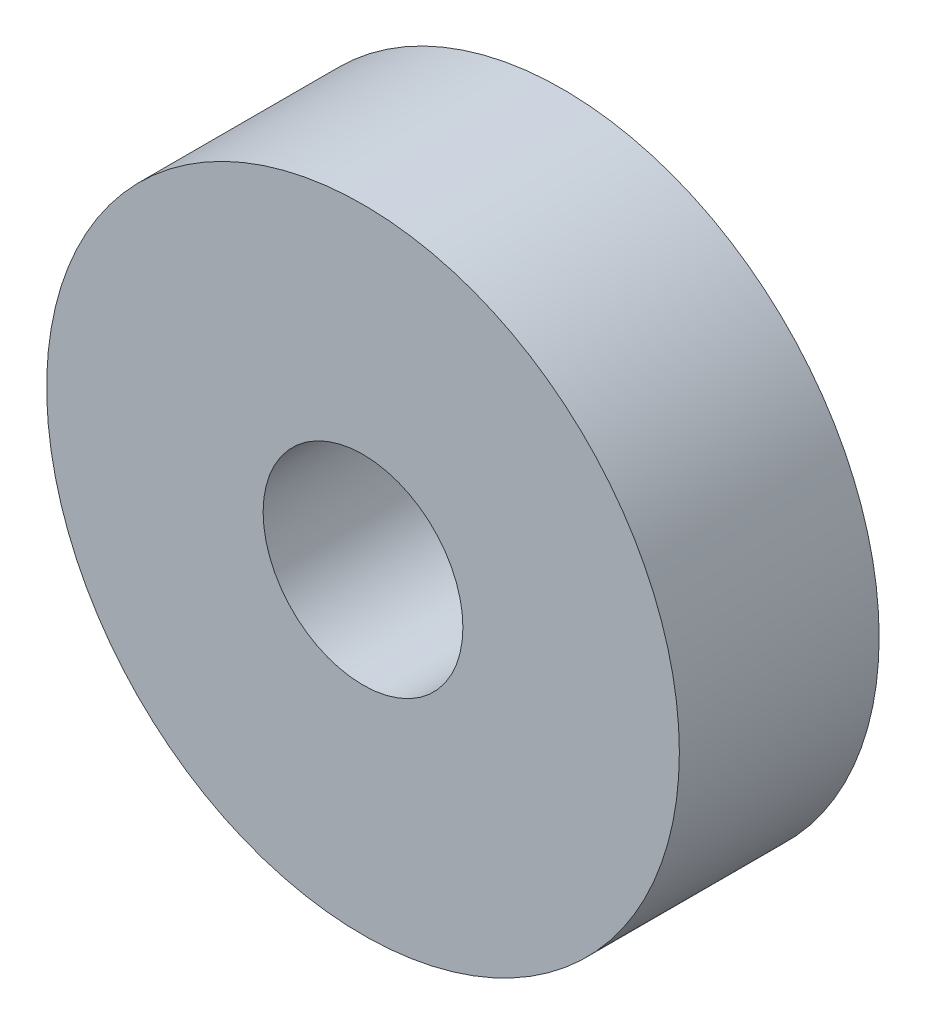
SolidWorks part; units mm, degrees
ref_plane "Plan de face" through (0, 0, 0) normal (0, 0, 1) x (1, 0, 0)
ref_plane "Plan de dessus" through (0, 0, 0) normal (0, 1, 0) x (1, 0, 0)
ref_plane "Plan de droite" through (0, 0, 0) normal (1, 0, 0) x (0, 0, -1)
sketch "Esquisse1" plane through (0, 0, 0) normal (0, 0, 1) x (1, 0, 0)
  circle A0 centre (0, 0) radius 9.5
extrude "Boss.-Extru.1" add sketch "Esquisse1" along normal blind 6
sketch "Esquisse2" plane through (0, 0, 6) normal (0, 0, 1) x (1, 0, 0)
  circle A0 centre (0, 0) radius 3
extrude "Enlèv. mat.-Extru.1" cut sketch "Esquisse2" against normal blind 6
